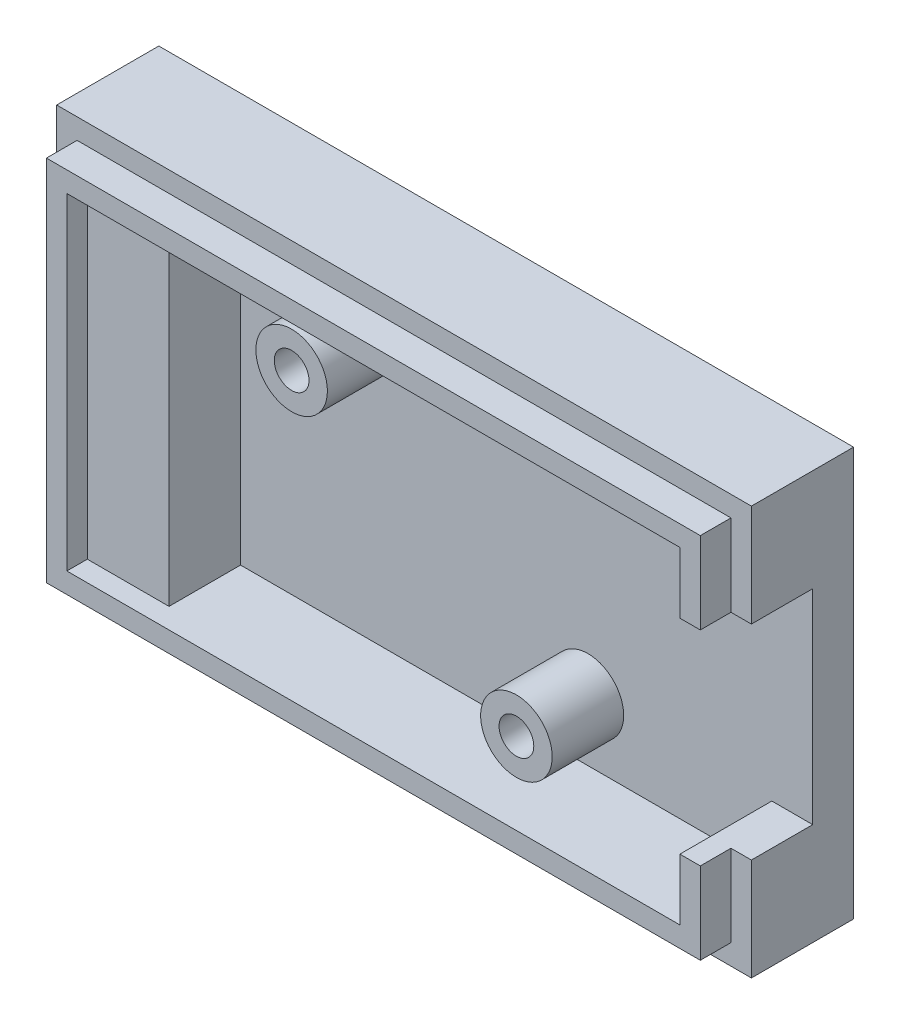
SolidWorks part; units mm, degrees
ref_plane "前视基准面" through (0, 0, 0) normal (0, 0, 1) x (1, 0, 0)
ref_plane "上视基准面" through (0, 0, 0) normal (0, 1, 0) x (1, 0, 0)
ref_plane "右视基准面" through (0, 0, 0) normal (1, 0, 0) x (0, 0, -1)
sketch "草图1" plane through (0, 0, 0) normal (0, 0, 1) x (1, 0, 0)
  line L1 (-17, 10) -> (17, 10)
  line L2 (-17, 10) -> (-17, -10)
  line L3 (-17, -10) -> (17, -10)
  line L4 (17, 10) -> (17, -10)
  line L5 (-17, 10) -> (17, -10) construction
  line L6 (-17, -10) -> (17, 10) construction
  point P0 (0, 0)
  dimension "D1" = 20
  dimension "D2" = 34
extrude "凸台-拉伸1" add sketch "草图1" along normal blind 6.5
sketch "草图2" plane through (0, 0, 6.5) normal (0, 0, 1) x (1, 0, 0)
  line L0 (17, -10) -> (17, 10) construction
  line L1 (-15, 8) -> (15, 8)
  line L2 (-15, 8) -> (-15, -8)
  line L3 (-15, -8) -> (15, -8)
  line L4 (15, 8) -> (15, -8)
  line L5 (-15, 8) -> (15, -8) construction
  line L6 (-15, -8) -> (15, 8) construction
  line L7 (17, 10) -> (-17, 10) construction
  point P0 (0, 0)
  dimension "D1" = 2
  dimension "D2" = 2
extrude "切除-拉伸1" cut sketch "草图2" against normal blind 4.5
sketch "草图3" plane through (17, 0, 0) normal (1, 0, 0) x (0, 0, -1)
  line L0 (-6.5, -10) -> (-6.5, 10) construction
  line L1 (-6.5, 5) -> (-2, 5)
  line L2 (-6.5, 5) -> (-6.5, -5)
  line L3 (-6.5, -5) -> (-2, -5)
  line L4 (-2, 5) -> (-2, -5)
  line L5 (-6.5, 10) -> (0, 10) construction
  line L6 (-6.5, -10) -> (0, -10) construction
  dimension "D1" = 5
  dimension "D2" = 5
  dimension "D3" = 4.5
extrude "切除-拉伸2" cut sketch "草图3" against normal blind 2
sketch "草图4" plane through (0, 0, 6.5) normal (0, 0, 1) x (1, 0, 0)
  line L0 (16, 5) -> (16, 9)
  line L1 (15, 5) -> (17, 5) construction
  line L2 (16, 9) -> (-16, 9)
  line L3 (-16, 9) -> (-16, -9)
  line L4 (-16, -9) -> (16, -9)
  line L5 (16, -9) -> (16, -5)
  line L6 (15, -5) -> (17, -5) construction
  line L7 (16, -5) -> (17, -5)
  line L8 (17, -5) -> (17, -10)
  line L9 (17, -10) -> (-17, -10)
  line L10 (-17, -10) -> (-17, 10)
  line L11 (-17, 10) -> (17, 10)
  line L12 (17, 10) -> (17, 5)
  line L13 (17, 5) -> (16, 5)
  dimension "D1" = 1
  dimension "D2" = 1
  dimension "D3" = 1
extrude "切除-拉伸3" cut sketch "草图4" against normal blind 1.5
sketch "草图5" plane through (0, 0, 2) normal (0, 0, 1) x (1, 0, 0)
  line L0 (-15, -8) -> (15, -8) construction
  line L1 (-15, 8) -> (-11, 8)
  line L2 (-15, 8) -> (-15, -8)
  line L3 (-15, -8) -> (-11, -8)
  line L4 (-11, 8) -> (-11, -8)
  dimension "D1" = 4
extrude "凸台-拉伸2" add sketch "草图5" along normal blind 3.5
sketch "草图6" plane through (0, 0, 2) normal (0, 0, 1) x (1, 0, 0)
  line L0 (-15, 8) -> (-15, -8) construction
  line L1 (16, -5) -> (16, -9) construction
  line L2 (15, 8) -> (-11, 8) construction
  line L3 (-15, -8) -> (15, -8) construction
  circle A0 centre (-5, 5) radius 1.75
  circle A1 centre (6, -5) radius 1.75
  dimension "D1" = 3.5
  dimension "D2" = 3.5
  dimension "D6" = 3
  dimension "D3" = 10
  dimension "D4" = 10
  dimension "D5" = 3
extrude "凸台-拉伸3" add sketch "草图6" along normal blind 3.5
sketch "草图7" plane through (0, 0, 5.5) normal (0, 0, 1) x (1, 0, 0)
  circle A0 centre (-5, 5) radius 0.85
  circle A1 centre (6, -5) radius 0.85
  dimension "D1" = 1.7
  dimension "D2" = 1.7
extrude "切除-拉伸4" cut sketch "草图7" against normal through all
sketch "草图8" plane through (0, 0, 0) normal (0, 0, -1) x (-1, 0, 0)
  circle A0 centre (-6, -5) radius 1.5
  circle A1 centre (5, 5) radius 1.5
  dimension "D1" = 3
  dimension "D2" = 3
extrude "切除-拉伸5" cut sketch "草图8" against normal blind 1
